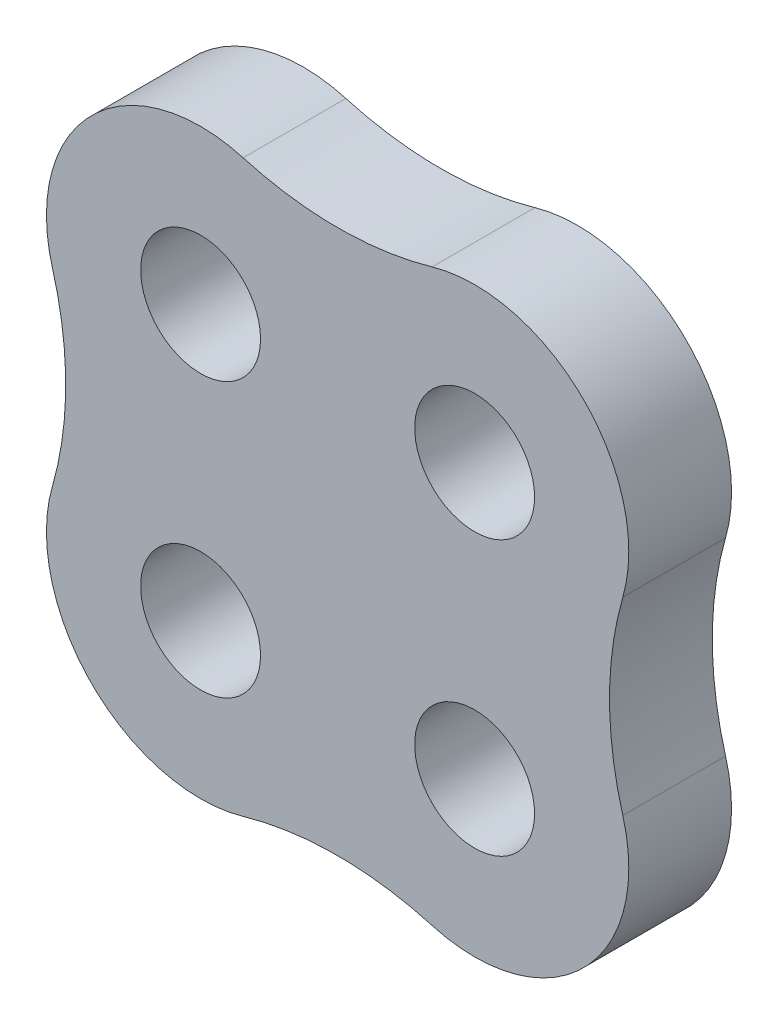
SolidWorks part; units mm, degrees
ref_plane "Спереди" through (0, 0, 0) normal (0, 0, 1) x (1, 0, 0)
ref_plane "Сверху" through (0, 0, 0) normal (0, 1, 0) x (1, 0, 0)
ref_plane "Справа" through (0, 0, 0) normal (1, 0, 0) x (0, 0, -1)
sketch "Эскиз1" plane through (0, 0, 0) normal (0, 0, 1) x (1, 0, 0)
  line L0 (0, 0) -> (78.1966, 0) construction
  circle A0 centre (0, 0) radius 4.5
  circle A1 centre (8, 0) radius 4.5
  circle A2 centre (0, 0) radius 1.75
  circle A3 centre (8, 0) radius 1.75
  circle A4 centre (0, 8) radius 4.5
  circle A5 centre (8, 8) radius 4.5
  circle A6 centre (0, 8) radius 1.75
  circle A7 centre (8, 8) radius 1.75
  dimension "D1" = 9
  dimension "D2" = 9
  dimension "D4" = 3.5
  dimension "D3" = 8
  dimension "D5" = 2
extrude "Бобышка-Вытянуть1" add sketch "Эскиз1" along normal blind 3
fillet "Скругление1" radius 10 4 edges at (4, -2.0616, 1.5) (10.0616, 4, 1.5) (4, 10.0616, 1.5) (-2.0616, 4, 1.5)
